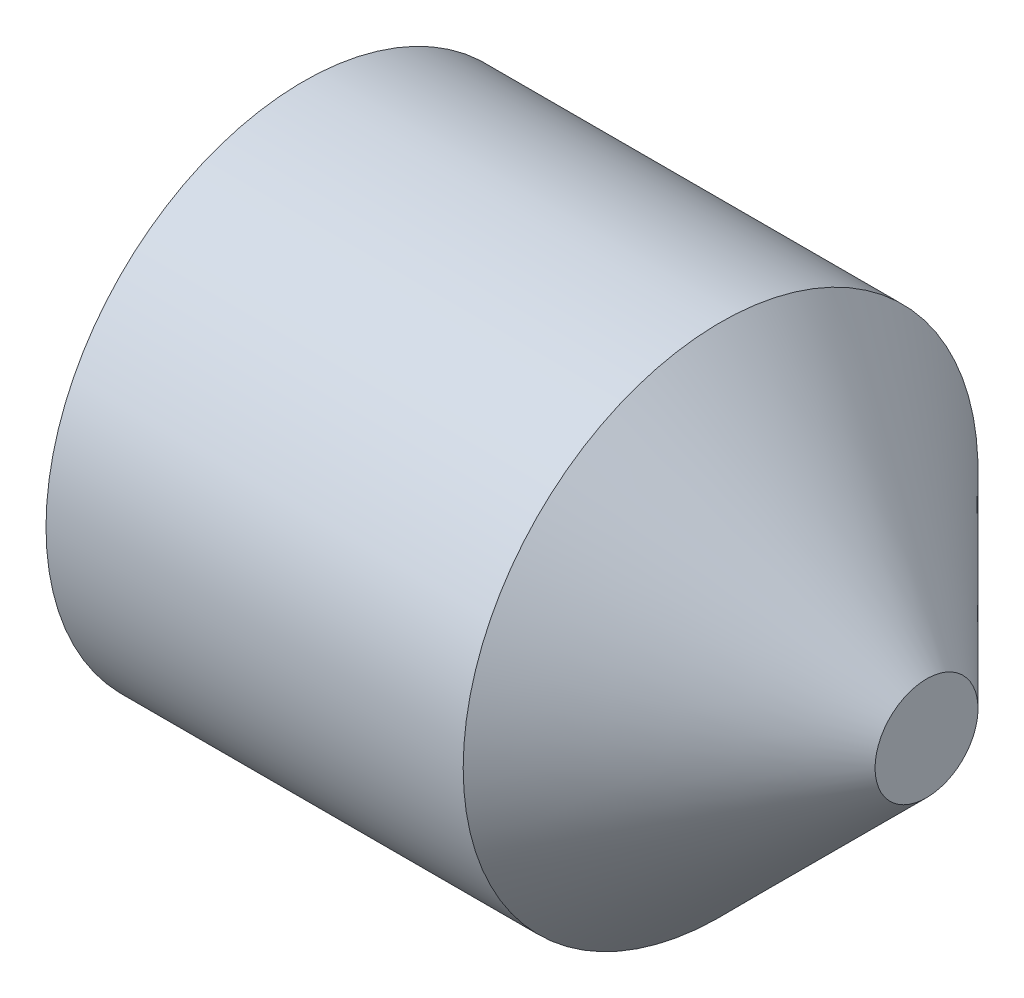
SolidWorks part; units mm, degrees
revolve "BaseBody" add sketch "BodySke" angle 360 about L5
sketch "BodySke" plane through (0, 0, 0) normal (0, 0, 1) x (1, 0, 0)
  line L0 (0, 0) -> (0, 10.352)
  line L1 (0, 10.352) -> (0.9515, 12)
  line L2 (0.9515, 12) -> (20.4, 12)
  line L3 (30, 0) -> (30, 2.4)
  line L4 (30, 0) -> (0, 0)
  line L5 (-12.7, 0) -> (88.9, 0) construction
  line L6 (30, 2.4) -> (20.4, 12)
  line L7 (3, 15.875) -> (3, -3.175) construction
  line L8 (0, -10.352) -> (0.9515, -12) construction
  line L9 (30, -2.4) -> (20.4, -12) construction
  dimension "Drive_ch_ang" = 60
  dimension "Cone_ang" = 90
cosmetic thread "ThreadCosmetic" [suppressed] parameters "Thread_minor"=20.704
ref_plane "Plane1" through (0, 0, 0) normal (0, 0, 1) x (1, 0, 0)
ref_plane "Plane2" through (0, 0, 0) normal (0, 1, 0) x (1, 0, 0)
ref_plane "Plane3" through (0, 0, 0) normal (1, 0, 0) x (0, 0, -1)
sketch "Sketch2" plane through (0, 0, 0) normal (-1, 0, 0) x (0, 0, 1)
  line L0 (3.4641, 6) -> (-3.4641, 6)
  line L1 (-3.4641, 6) -> (-6.9282, 0)
  line L2 (3.4641, 6) -> (6.9282, 0)
  line L3 (3.4641, -6) -> (6.9282, 0)
  line L4 (3.4641, -6) -> (-3.4641, -6)
  line L5 (-3.4641, -6) -> (-6.9282, 0)
  dimension "D2" = 6
  dimension "D3" = 6
extrude "Hex" cut sketch "Sketch2" against normal blind 10
sketch "Sketch4" plane through (0, 4.7709, -0.5249) normal (-1, 0, 0) x (0, 0, 1)
  line L0 (0.5249, -4.7709) -> (10.6976, -4.7709)
  line L1 (0.5249, -4.7709) -> (6.6732, -1.2211) construction
  line L2 (0.5249, -4.7709) -> (5.6112, 4.0389)
  line L3 (8.9666, -2.6687) -> (10.2861, -1.9069)
  line L4 (6.5663, 1.4888) -> (7.8858, 2.2506)
  arc A0 (8.9666, -2.6687) -> (6.5663, 1.4888) centre (0.5249, -4.7709) ccw
  arc A1 (10.6976, -4.7709) -> (10.2861, -1.9069) centre (0.5249, -4.7709) ccw
  arc A2 (5.6112, 4.0389) -> (7.8858, 2.2506) centre (0.5249, -4.7709) cw
  circle A3 centre (0.5249, -4.7709) radius 8.6995 construction
  circle A4 centre (0.5249, -4.7709) radius 10.1727 construction
  dimension "D1" = 30
  dimension "Spline_a_dim" = 60
extrude "Spline6" [suppressed] cut sketch "Sketch4" against normal blind 12
pattern_circular "CirPattern1" [suppressed] count 6 every 60 about axis through (-12.7, 0, 0) along (1, 0, 0)
sketch "Sketch5" plane through (0, 1.4735, 6.925) normal (-1, 0, 0) x (0, 0, 1)
  line L0 (-6.925, -1.4735) -> (3.2477, -1.4735)
  line L1 (-6.925, -1.4735) -> (-1.9049, 3.5466) construction
  line L2 (-6.925, -1.4735) -> (-6.925, 8.6992)
  line L3 (0.9237, 2.9807) -> (1.7623, 3.8193)
  line L4 (-2.4708, 6.3752) -> (-1.6322, 7.2139)
  line L5 (-2.4708, 6.3752) -> (0.9237, 2.9807)
  arc A1 (3.2477, -1.4735) -> (1.7623, 3.8193) centre (-6.925, -1.4735) ccw
  arc A2 (-6.925, 8.6992) -> (-1.6322, 7.2139) centre (-6.925, -1.4735) cw
  circle A3 centre (-6.925, -1.4735) radius 8.6995 construction
  circle A4 centre (-6.925, -1.4735) radius 10.1727 construction
  dimension "D1" = 45
  dimension "Spline_a_dim" = 90
extrude "Spline4" [suppressed] cut sketch "Sketch5" against normal blind 12
pattern_circular "CirPattern2" [suppressed] count 4 every 90 about axis through (-12.7, 0, 0) along (1, 0, 0)
sketch "ThdSchSke" plane through (0, 0, 0) normal (0, 0, 1) x (1, 0, 0)
  line L0 (0.9515, -10.352) -> (-0.2025, -12)
  line L1 (0.9515, -10.352) -> (2.1054, -12)
  line L2 (2.1054, -12) -> (2.1054, -15)
  line L3 (-3.175, 0) -> (5.1513, 0) construction
  line L4 (0.9515, 12) -> (0.9515, -12) construction
  line L5 (2.1054, -15) -> (-0.2025, -15)
  line L6 (-0.2025, -15) -> (-0.2025, -12)
revolve "ThreadSchematic" [suppressed] cut sketch "ThdSchSke" angle 360 about L3
pattern_linear "ThdSchPat" [suppressed]
equation "\"D2@Sketch2\" = \"Hex_size@Sketch2\" / 2"
equation "\"D3@Sketch2\" = \"Hex_size@Sketch2\" / 2"
equation "\"Thread_minor@ThreadCosmetic\" = \"Minor_dia@BodySke\""
equation "\"D1@Sketch4\" = \"Spline_a_dim@Sketch4\" / 2"
equation "\"D3@Sketch4\" = \"Spline_p_dim@Sketch4\" / 2"
equation "\"D2@CirPattern1\" = \"Spline_a_dim@Sketch4\""
equation "\"Num_teeth@CirPattern1\" = 360 / \"D2@CirPattern1\""
equation "\"Spline_a_dim@Sketch5\" = 90"
equation "\"Spline_p_dim@Sketch5\" = \"Spline_p_dim@Sketch4\""
equation "\"Spline_m_dim@Sketch5\" = \"Spline_m_dim@Sketch4\""
equation "\"Spline_n_dim@Sketch5\" = \"Spline_n_dim@Sketch4\""
equation "\"D1@Sketch5\" = \"Spline_a_dim@Sketch5\" / 2"
equation "\"D3@Sketch5\" = \"Spline_p_dim@Sketch5\" / 2"
equation "\"Key_eng@Spline4\" = \"Key_eng@Spline6\""
equation "\"Thread_minor@ThdSchSke\" = \"Thread_minor@ThreadCosmetic\""
equation "\"Diameter@ThdSchSke\" = \"Diameter@BodySke\""
equation "\"Overcut@ThdSchSke\" = \"Diameter@BodySke\" * 1.25"
equation "\"Num_threads@ThdSchPat\" = int( (\"Length@BodySke\" - ( ( ( \"Diameter@BodySke\" - \"Minor_dia@BodySke\" ) * 0.5 ) / tan( \"Drive_ch_ang@BodySke\" * 0.017453292 ) ) - ( ( \"Diameter@BodySke\" * 0.5 ) / tan( \"Cone_ang@BodySke\" * 0.008726646 ) ) ) / \"Advance@BodySke\" + 0.999 )  + 1"
equation "\"Num_threads@ThdSchPat\" = int( (\"Length@BodySke\" - ( ( ( \"Diameter@BodySke\" - \"Minor_dia@BodySke\" ) * 0.5 ) / tan( \"Drive_ch_ang@BodySke\" * 0.017453292 ) ) - ( (( \"Diameter@BodySke\" - \"Tip_dia@BodySke\") * 0.5 ) / tan( \"Cone_ang@BodySke\" * 0.008726646 ) ) ) / \"Advance@BodySke\" + 0.999 )  + 1"
equation "\"Advance@ThdSchPat\" = (\"Length@BodySke\" - ( ( ( \"Diameter@BodySke\" - \"Minor_dia@BodySke\" ) * 0.5 ) / tan( \"Drive_ch_ang@BodySke\" * 0.017453292 ) ) - ( ( \"Diameter@BodySke\" * 0.5 ) / tan( \"Cone_ang@BodySke\" * 0.008726646 ) ) ) /  (\"Num_threads@ThdSchPat\" - 1) 'relax it"
equation "\"Advance@ThdSchPat\" = (\"Length@BodySke\" - ( ( ( \"Diameter@BodySke\" - \"Minor_dia@BodySke\" ) * 0.5 ) / tan( \"Drive_ch_ang@BodySke\" * 0.017453292 ) ) - ( ( (\"Diameter@BodySke\" - \"Tip_dia@BodySke\") * 0.5 ) / tan( \"Cone_ang@BodySke\" * 0.008726646 ) ) ) /  (\"Num_threads@ThdSchPat\" - 1) 'relax it"
equation "' \"Num_threads@ThdSchPat\" = \"Num_threads@ThdSchPat\" - sgn( \"Num_threads@ThdSchPat\" - 1) '---chamfered tips only---"
